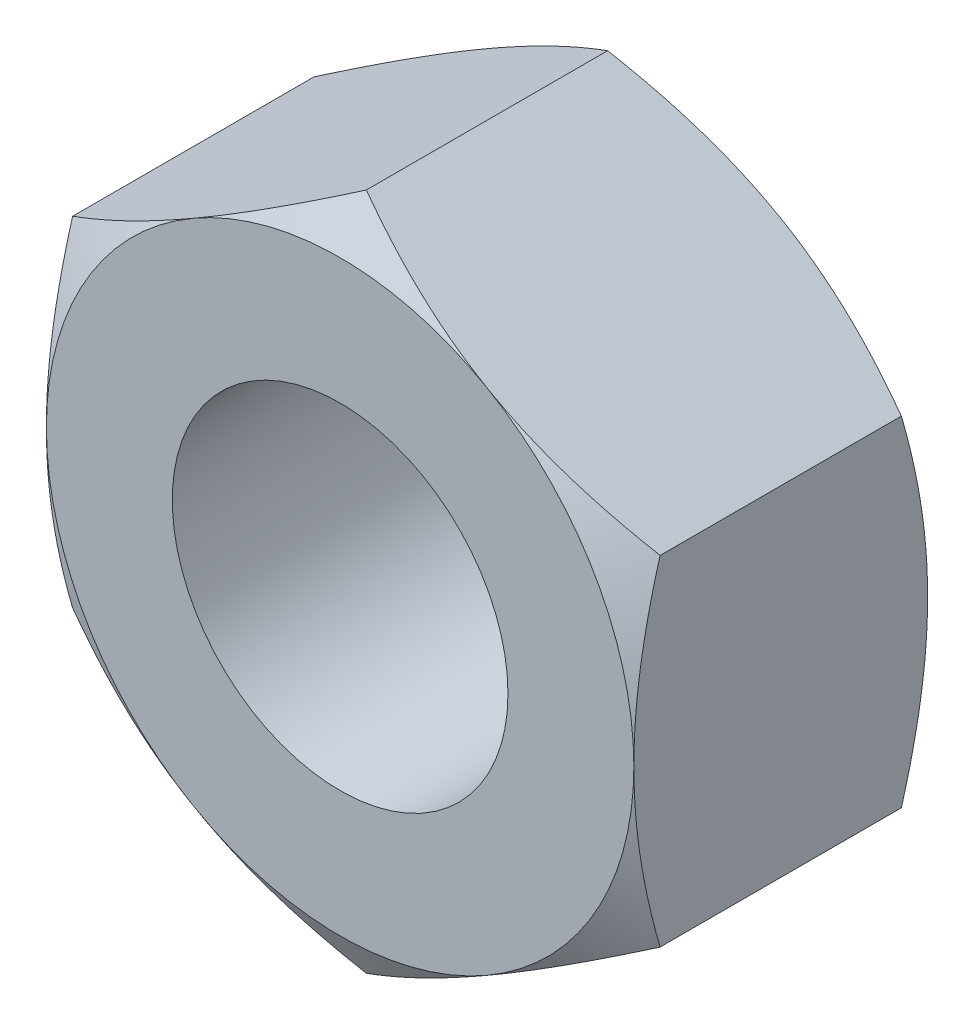
SolidWorks part; units mm, degrees
material "AISI 1020"
ref_plane "Front" through (0, 0, 0) normal (0, 0, 1) x (1, 0, 0)
ref_plane "Top" through (0, 0, 0) normal (0, 1, 0) x (1, 0, 0)
ref_plane "Right" through (0, 0, 0) normal (1, 0, 0) x (0, 0, -1)
sketch "Sketch1" plane through (0, 0, 0) normal (0, 0, 1) x (1, 0, 0)
  line L1 (-5.5562, 3.2079) -> (-5.5562, -3.2079)
  line L2 (-5.5562, -3.2079) -> (0, -6.4158)
  line L3 (0, -6.4158) -> (5.5562, -3.2079)
  line L4 (5.5562, -3.2079) -> (5.5562, 3.2079)
  line L5 (5.5562, 3.2079) -> (0, 6.4158)
  line L6 (0, 6.4158) -> (-5.5562, 3.2079)
  circle A0 centre (0, 0) radius 5.5562 construction
  circle A1 centre (0, 0) radius 3.175
  point P10 (0, 3.175)
  dimension "hex" = 11.1125
  dimension "dia" = 6.35
extrude "Extrude1" add sketch "Sketch1" along normal mid plane 5.5562
sketch "Sketch4" plane through (0, 0, -2.7781) normal (0, 0, -1) x (-1, 0, 0)
  circle A0 centre (0, 0) radius 3.175 construction
  circle A1 centre (0, 0) radius 3.175
curve "Helix/Spiral3" pitch 1.27 height 6.6675 turns 5.25
sketch "Sketch3" plane through (0, 0, 0) normal (1, 0, 0) x (0, 0, -1)
  line L0 (2.7781, 3.175) -> (3.8894, 3.175)
  line L1 (3.8894, 3.175) -> (3.4131, 2.3501)
  line L2 (3.4131, 2.3501) -> (3.2544, 2.3501)
  line L3 (3.2544, 2.3501) -> (2.7781, 3.175)
  line L4 (3.0163, 2.7626) -> (3.6513, 2.7626) construction
  dimension "D1" = 60
  dimension "D2" = 0.635
  dimension "D3" = 0.1588
sketch "Sketch7" plane through (0, 0, 2.7781) normal (0, 0, 1) x (1, 0, 0)
  circle A0 centre (0, 0) radius 5.5562 construction
  circle A1 centre (0, 0) radius 5.5562
extrude "Extrude2" cut sketch "Sketch7" against normal blind 25.4 draft 60 flip side to cut
mirror "Mirror1" about plane through (0, 0, 0) normal (0, 0, 1) of "Extrude2"
equation "\"D3@Helix/Spiral3\" = \"length@Extrude1\" * 1.2"
equation "\"D2@Sketch3\" = \"D4@Helix/Spiral3\" * .5"
equation "\"D3@Sketch3\" = \"D4@Helix/Spiral3\" * .125"
